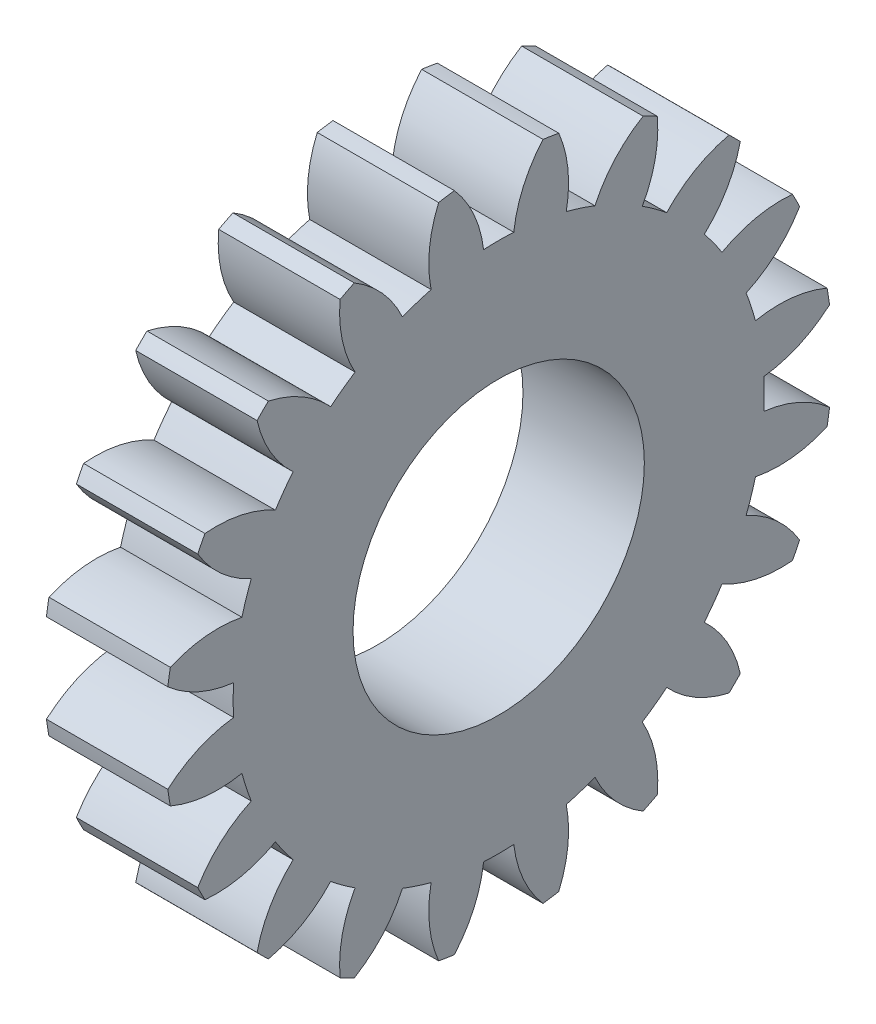
SolidWorks part; units mm, degrees
ref_plane "Plane1" through (0, 0, 0) normal (0, 0, 1) x (1, 0, 0)
ref_plane "Plane2" through (0, 0, 0) normal (0, 1, 0) x (1, 0, 0)
ref_plane "Plane3" through (0, 0, 0) normal (1, 0, 0) x (0, 0, -1)
sketch "HoldingSke" plane through (0, 0, 0) normal (0, 1, 0) x (1, 0, 0)
  line L0 (0, 0) -> (0.7518, -0.2736)
  line L1 (-15, 0) -> (100, 0) construction
  line L2 (0, 0) -> (-2.1039, 2.3779)
  line L3 (0, 0) -> (-11.863, 4.5341)
  line L4 (0, 0) -> (8.1152, 2.9537)
  line L5 (0, 0) -> (-46.8476, -17.4728)
  line L6 (0, 0) -> (-4.1448, -2.7965)
  line L7 (-2.1039, 2.3779) -> (8.6586, 51.2059)
  line L8 (-76.2, 54.61) -> (-73.9, 54.61)
  line L9 (-71.009, 38.7566) -> (-53.1078, 45.2721)
  line L10 (-76.2, 71.12) -> (104.1128, 71.12)
  line L11 (0, 0) -> (-5, 0)
  line L12 (-76.2, 101.6) -> (-76.155, 101.6)
  line L13 (24.9733, 27.94) -> (52.9518, 28.4284)
  line L14 (24.9733, 27.94) -> (24.9743, 27.94)
  line L15 (24.9733, 27.94) -> (100.4006, 29.5858)
  line L16 (-63.627, -1.25) -> (-12.827, -1.25)
  circle A0 centre (0, 0) radius 6
  circle A1 centre (0, 0) radius 10.9365
  circle A2 centre (0, 0) radius 37.5
  circle A3 centre (0, 0) radius 6
  dimension "MHD" = 21.873
  dimension "Hub_dia" = 75
  dimension "Bore" = 12
  dimension "MBD" = 12
  dimension "Num_teeth" = 20
  dimension "Pitch" = 0.8
  dimension "Overall_len" = 50
  dimension "Show_teeth" = 20
  dimension "Thickness" = 5
  dimension "OAL" = 50.0001
  dimension "T_dim" = 2.3
  dimension "Ap" = 20
  dimension "H" = 19.05
  dimension "Pitch_radius" = 180.3128
  dimension "Width" = 5
  dimension "Backlash" = 0.045
  dimension "Addendum_fac" = 1
  dimension "Dedendum_fac" = 1.25
  dimension "Clearance_fac" = 0.25
  dimension "Dedendum_add" = 0.001
  dimension "Module" = 1.25
sketch "BasProSke" plane through (0, 0, 0) normal (0, 1, 0) x (1, 0, 0)
  line L0 (-10, 0) -> (60, 0) construction
  line L1 (0, 0) -> (0, 13.75)
  line L2 (0, 0) -> (5, 0)
  line L3 (5, 0) -> (5, 13.75)
  line L4 (5, 13.75) -> (0, 13.75)
  dimension "Thickness" = 5
  dimension "Diameter" = 27.5
revolve "Base-Revolve" add sketch "BasProSke" angle 360 about L0
sketch "TooCutSke" plane through (0, 0, 0) normal (1, 0, 0) x (0, 0, -1)
  line L1 (0, 0) -> (0, 107) construction
  line L2 (0, 0) -> (-1.0594, 12.455) construction
  line L3 (0, 0) -> (-3.9007, 24.6278) construction
  line L4 (-1.0594, 12.455) -> (-1.9503, 12.3139) construction
  arc A0 (0.6211, 10.9188) -> (-0.6211, 10.9188) centre (0, 0) ccw
  arc A1 (1.8466, 13.6511) -> (-1.8466, 13.6511) centre (0, 0) ccw
  circle A2 centre (0, 0) radius 12.5 construction
  circle A3 centre (0, 0) radius 11.7462 construction
  arc A4 (-0.6211, 10.9188) -> (-1.8466, 13.6511) centre (-5.5866, 10.3326) ccw
  arc A5 (1.8466, 13.6511) -> (0.6211, 10.9188) centre (5.5866, 10.3326) ccw
  dimension "Root_dia" = 21.873
  dimension "Overcut_dia" = 27.5508
  dimension "Pitch_dia" = 25
  dimension "Base_dia" = 23.4923
  dimension "Flank_rad" = 5
  dimension "Half_ang" = 9
  dimension "Half_CT" = 0.902
extrude "ToothCut" cut sketch "TooCutSke" along normal through all
fillet "Breaks" [suppressed] radius 0.025
fillet "RootFillets" [suppressed] radius 0.3135
pattern_circular "TeethCuts" count 20 every 18 about axis through (-10, 0, 0) along (1, 0, 0) of "ToothCut", "RootFillets", "Breaks"
sketch "HubNeaOneSke" plane through (0, 0, 0) normal (-1, 0, 0) x (0, 0, 1)
  circle A0 centre (0, 0) radius 10.9365
  dimension "Diameter" = 21.873
extrude "HubNearOne" [suppressed] add sketch "HubNeaOneSke" along normal blind 45.0001
sketch "HubNeaBotSke" plane through (0, 0, 0) normal (-1, 0, 0) x (0, 0, 1)
  circle A0 centre (0, 0) radius 10.9365
  dimension "Diameter" = 21.873
extrude "HubNearBoth" [suppressed] add sketch "HubNeaBotSke" along normal blind 22.5
ref_plane "FarPln" through (5, 0, 0) normal (1, 0, 0) x (0, 0, -1)
sketch "HubFarSke" plane through (5, 0, 0) normal (1, 0, 0) x (0, 0, -1)
  circle A0 centre (0, 0) radius 10.9365
  dimension "Diameter" = 21.873
extrude "HubFar" [suppressed] add sketch "HubFarSke" along normal blind 22.5
sketch "BorSke" plane through (0, 0, 0) normal (1, 0, 0) x (0, 0, -1)
  circle A0 centre (0, 0) radius 6
  dimension "Diameter" = 12
extrude "Bore" cut sketch "BorSke" along normal mid plane 100.0001
sketch "KeySke" plane through (0, 0, 0) normal (1, 0, 0) x (0, 0, -1)
  line L0 (-2, 0) -> (-2, 8.3)
  line L1 (-2, 8.3) -> (2, 8.3)
  line L2 (2, 8.3) -> (2, 0)
  line L3 (0, 0) -> (0, 34) construction
  line L4 (-2, 0) -> (2, 0)
  dimension "Offset" = 8.3
  dimension "Width" = 4
extrude "Keyway" [suppressed] cut sketch "KeySke" along normal mid plane 100.0001
pattern_circular "Keyway2" [suppressed] count 2 every 90 about axis through (-10, 0, 0) along (1, 0, 0)
equation "' \"Module@HoldingSke\" = 6.35"
equation "' \"Num_teeth@HoldingSke\" = 12"
equation "' \"Ap@HoldingSke\" =  20"
equation "' \"Ap@HoldingSke\" = 20"
equation "' \"Width@HoldingSke\" = 0.5 * 25.4"
equation "' \"Hub_dia@HoldingSke\"= 1 * 25.4"
equation "' \"Hub_dia@HoldingSke\" = 1 * 25.4"
equation "' \"Overall_len@HoldingSke\" = 1.0 * 25.4"
equation "' \"Bore@HoldingSke\" = 0.75 * 25.4"
equation "' \"T_dim@HoldingSke\" = 0.1 * 25.4"
equation "' \"Width@KeySke\" = 0.25 * 25.4"
equation "' \"Show_teeth@HoldingSke\" = 13"
equation "' \"Backlash@HoldingSke\" = 0.009 * 25.4"
equation "' \"Addendum_fac@HoldingSke\" = 1.0"
equation "' \"Dedendum_fac@HoldingSke\" = 1.25"
equation "' \"Dedendum_add@HoldingSke\" = 0.00005 * 25.4"
equation "' \"Clearance_fac@HoldingSke\" = 0.25"
equation "\"Pitch@HoldingSke\" = 1 / \"Module@HoldingSke\""
equation "\"Overcut_dia@TooCutSke\" = (\"Num_teeth@HoldingSke\" + 2 * \"Addendum_fac@HoldingSke\") / \"Pitch@HoldingSke\" + 0.002 * 25.4"
equation "\"Pitch_dia@TooCutSke\" = \"Num_teeth@HoldingSke\" / \"Pitch@HoldingSke\""
equation "\"Base_dia@TooCutSke\" = \"Num_teeth@HoldingSke\" / \"Pitch@HoldingSke\" * cos((\"Ap@HoldingSke\"  * 3.14159265 / 180))"
equation "\"Root_dia@TooCutSke\" = (\"Num_teeth@HoldingSke\" + 2) / \"Pitch@HoldingSke\" - 2 * (\"Addendum_fac@HoldingSke\" + \"Dedendum_fac@HoldingSke\") / \"Pitch@HoldingSke\" - \"Dedendum_add@HoldingSke\" * 2"
equation "\"Half_ang@TooCutSke\" = 180 / \"Num_teeth@HoldingSke\""
equation "\"Half_CT@TooCutSke\" = \"Num_teeth@HoldingSke\" / \"Pitch@HoldingSke\" * sin((3.14159265 / 2 / \"Num_teeth@HoldingSke\")) / 2 - 7 * \"Backlash@HoldingSke\" / 4"
equation "\"Flank_rad@TooCutSke\" = \"Num_teeth@HoldingSke\" / \"Pitch@HoldingSke\" / 5"
equation "\"Radius@RootFillets\" = \"Clearance_fac@HoldingSke\" / \"Pitch@HoldingSke\" + \"Dedendum_add@HoldingSke\""
equation "\"Break_rad@Breaks\" = 0.02 / \"Pitch@HoldingSke\""
equation "\"Thickness@HoldingSke\" = \"Width@HoldingSke\""
equation "\"OAL@HoldingSke\" = \"Thickness@HoldingSke\""
equation "\"MHD@HoldingSke\" = (\"Num_teeth@HoldingSke\" + 2) / \"Pitch@HoldingSke\" - 2 * (\"Addendum_fac@HoldingSke\" + \"Dedendum_fac@HoldingSke\")  / \"Pitch@HoldingSke\" - \"Dedendum_add@HoldingSke\" * 2"
equation "\"MBD@HoldingSke\" = (\"Num_teeth@HoldingSke\" + 2) / \"Pitch@HoldingSke\" - 2 * (\"Addendum_fac@HoldingSke\" + \"Dedendum_fac@HoldingSke\")  / \"Pitch@HoldingSke\" - \"Dedendum_add@HoldingSke\" * 2 - 0.002 * 25.4"
equation "\"MHD@HoldingSke\" = ((sgn( \"MHD@HoldingSke\" - \"Hub_dia@HoldingSke\" )-1)*( \"MHD@HoldingSke\" - \"Hub_dia@HoldingSke\" ))/-2+ \"Hub_dia@HoldingSke\""
equation "\"MBD@HoldingSke\" = ((sgn( \"MBD@HoldingSke\" - \"Bore@HoldingSke\" )-1)*( \"MBD@HoldingSke\" - \"Bore@HoldingSke\" ))/-2+ \"Bore@HoldingSke\""
equation "\"OAL@HoldingSke\" = ((sgn( \"OAL@HoldingSke\" - \"Overall_len@HoldingSke\" )+1)*( \"OAL@HoldingSke\" - \"Overall_len@HoldingSke\" ))/2 + \"Overall_len@HoldingSke\" + 0.000002 * 25.4"
equation "\"Num_teeth@TeethCuts\" = int( \"Show_teeth@HoldingSke\" ) + 1"
equation "\"Num_teeth@TeethCuts\" = ((sgn( \"Num_teeth@TeethCuts\" - \"Num_teeth@HoldingSke\" )-1)*( \"Num_teeth@TeethCuts\" - \"Num_teeth@HoldingSke\" ))/-2+ \"Num_teeth@HoldingSke\""
equation "\"Num_teeth@TeethCuts\" = ((sgn( \"Num_teeth@TeethCuts\" - 2.0)+1)*( \"Num_teeth@TeethCuts\" - 2.0))/2 +2.0"
equation "\"Angle@TeethCuts\" = 360.0 / \"Num_teeth@HoldingSke\""
equation "\"Diameter@BasProSke\" = (\"Num_teeth@HoldingSke\" + 2 * \"Addendum_fac@HoldingSke\") / \"Pitch@HoldingSke\""
equation "\"Thickness@BasProSke\"  = \"Thickness@HoldingSke\""
equation "' \"Fillet_rad@BasProSke\" =  \"Thickness@HoldingSke\" * 0.05"
equation "' \"Fillet_rad@BasProSke\" = \"Thickness@HoldingSke\" * 0.05"
equation "\"MHD@HoldingSke\" = ((sgn( \"MHD@HoldingSke\" - \"Root_dia@TooCutSke\" )-1)*( \"MHD@HoldingSke\" - \"Root_dia@TooCutSke\" ))/-2+ \"Root_dia@TooCutSke\""
equation "\"Diameter@HubNeaOneSke\" = \"MHD@HoldingSke\""
equation "\"Length@HubNearOne\" = \"OAL@HoldingSke\" - \"Thickness@BasProSke\""
equation "\"Diameter@HubNeaBotSke\" = \"MHD@HoldingSke\""
equation "\"Length@HubNearBoth\" = ( \"OAL@HoldingSke\" - \"Thickness@BasProSke\" ) / 2.0"
equation "\"Thickness@FarPln\" = \"Thickness@BasProSke\""
equation "\"Diameter@HubFarSke\" = \"MHD@HoldingSke\""
equation "\"Length@HubFar\" = ( \"OAL@HoldingSke\" - \"Thickness@BasProSke\" ) / 2.0"
equation "\"Diameter@BorSke\" = \"MBD@HoldingSke\""
equation "\"D1@Bore\" = \"OAL@HoldingSke\" * 2.0"
equation "\"D1@Keyway\" = \"OAL@HoldingSke\" * 2.0"
equation "\"Offset@KeySke\" = \"T_dim@HoldingSke\" + \"MBD@HoldingSke\" / 2.0"
